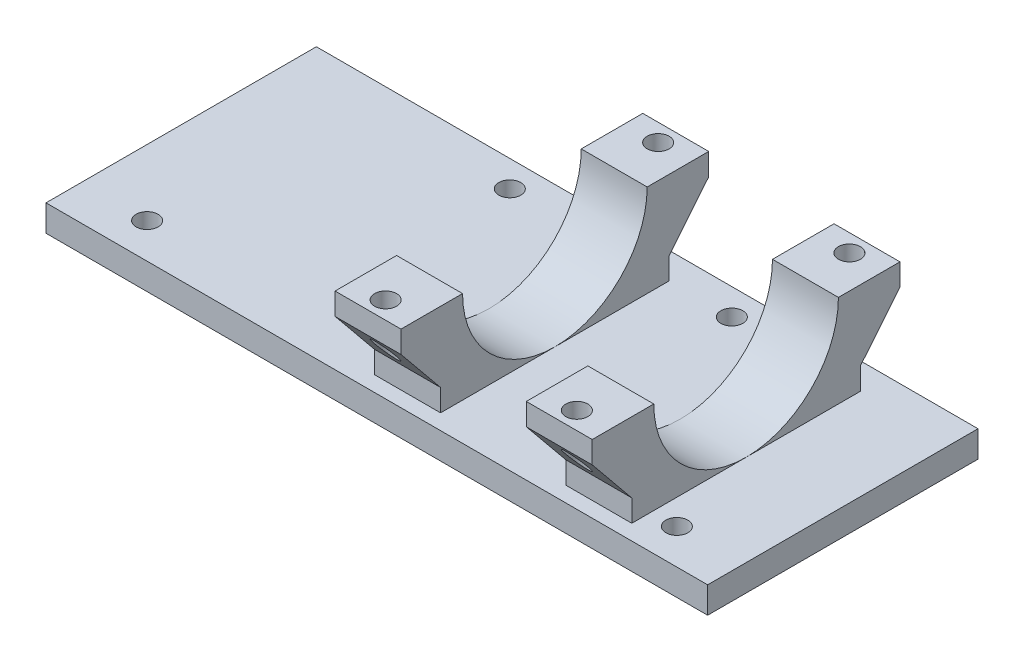
SolidWorks part; units mm, degrees
ref_plane "Alzado" through (0, 0, 0) normal (0, 0, 1) x (1, 0, 0)
ref_plane "Planta" through (0, 0, 0) normal (0, 1, 0) x (1, 0, 0)
ref_plane "Vista lateral" through (0, 0, 0) normal (1, 0, 0) x (0, 0, -1)
sketch "Croquis1" plane through (0, 0, 0) normal (0, 1, 0) x (1, 0, 0)
  line L1 (74.5, -26.5) -> (-74.5, -26.5)
  line L2 (74.5, -26.5) -> (74.5, 26.5)
  line L3 (74.5, 26.5) -> (-74.5, 26.5)
  line L4 (-74.5, -26.5) -> (-74.5, 26.5)
  line L5 (74.5, -26.5) -> (-74.5, 26.5) construction
  line L6 (74.5, 26.5) -> (-74.5, -26.5) construction
  point P0 (0, 0)
  dimension "D1" = 149
  dimension "D2" = 53
extrude "Saliente-Extruir1" add sketch "Croquis1" along normal blind 6
ref_plane "Plano1" through (51.5, 0, 0) normal (1, 0, 0) x (0, 0, -1)
sketch "Croquis2" plane through (51.5, 0, 0) normal (1, 0, 0) x (0, 0, -1)
  line L0 (-26.5, 6) -> (26.5, 6) construction
  line L1 (26, 6) -> (-26, 6)
  line L2 (26, 6) -> (26, 27)
  line L4 (-26, 6) -> (-26, 27)
  arc A0 (26, 27) -> (-26, 27) centre (0, 27) ccw
  point P6 (0, 6)
  dimension "D1" = 52
  dimension "D2" = 21
extrude "Saliente-Extruir2" add sketch "Croquis2" against normal blind 15 contours L2 A0 L4 L1
ref_plane "Plano4" through (8, 0, 0) normal (-1, 0, 0) x (0, 0, 1)
sketch "Croquis5" plane through (8, 0, 0) normal (-1, 0, 0) x (0, 0, 1)
  line L0 (-26, 6) -> (26, 6) construction
  line L1 (26, 6) -> (26, 27) construction
  line L2 (-26, 6) -> (-26, 27) construction
  line L3 (-26, 6) -> (26, 6)
  line L4 (26, 6) -> (26, 27)
  line L5 (-26, 6) -> (-26, 27)
  arc A0 (26, 27) -> (-26, 27) centre (0, 27) ccw construction
  arc A1 (26, 27) -> (-26, 27) centre (0, 27) ccw
extrude "Saliente-Extruir5" add sketch "Croquis5" along normal blind 15
sketch "Croquis3" plane through (51.5, 0, 0) normal (1, 0, 0) x (0, 0, -1)
  circle A0 centre (0, 27) radius 21
  dimension "D1" = 42
extrude "Cortar-Extruir2" cut sketch "Croquis3" against normal through all contours A0
ref_plane "Plano5" through (0, 0, 26) normal (0, 0, 1) x (1, 0, 0)
sketch "Croquis10" plane through (0, 0, 26.5) normal (0, 0, 1) x (1, 0, 0)
  line L4 (-74.5, 0) -> (74.5, 0)
  line L5 (74.5, 0) -> (74.5, 6)
  line L6 (74.5, 6) -> (-74.5, 6)
  line L7 (-74.5, 6) -> (-74.5, 0)
  line L8 (-74.5, 0) -> (74.5, 0)
  line L9 (74.5, 0) -> (74.5, 6)
  line L10 (74.5, 6) -> (-74.5, 6)
  line L11 (-74.5, 6) -> (-74.5, 0)
  dimension "D1" = 0
extrude "Saliente-Extruir23" add sketch "Croquis10" along normal blind 3
sketch "Croquis11" plane through (0, 6, 0) normal (0, 1, 0) x (1, 0, 0)
  line L0 (74.5, -29.5) -> (-74.5, -29.5) construction
  line L1 (74.5, 26.5) -> (72.25, 26.5)
  line L2 (74.5, 26.5) -> (74.5, -29.5)
  line L3 (74.5, -29.5) -> (72.25, -29.5)
  line L4 (72.25, 26.5) -> (72.25, -29.5)
  dimension "D1" = 2.25
extrude "Cortar-Extruir3" cut sketch "Croquis11" against normal through all
sketch "Croquis12" plane through (-74.5, 0, 0) normal (-1, 0, 0) x (0, 0, 1)
  line L4 (-26.5, 0) -> (29.5, 0)
  line L5 (29.5, 0) -> (29.5, 6)
  line L6 (29.5, 6) -> (-26.5, 6)
  line L7 (-26.5, 6) -> (-26.5, 0)
  line L8 (-26.5, 0) -> (29.5, 0)
  line L9 (29.5, 0) -> (29.5, 6)
  line L10 (29.5, 6) -> (-26.5, 6)
  line L11 (-26.5, 6) -> (-26.5, 0)
  dimension "D1" = 0
extrude "Saliente-Extruir24" add sketch "Croquis12" along normal blind 3.75
ref_plane "Plano6" through (-3, 0, 0) normal (1, 0, 0) x (0, 0, -1)
sketch "Croquis13" plane through (0, 6, 0) normal (0, 1, 0) x (1, 0, 0)
  line L0 (-78.25, -29.5) -> (-78.25, 26.5) construction
  line L1 (72.25, 26.5) -> (-78.25, 26.5)
  line L2 (72.25, 26.5) -> (72.25, 26)
  line L3 (72.25, 26) -> (-78.25, 26)
  line L4 (-78.25, 26.5) -> (-78.25, 26)
  line L5 (-7, 26) -> (8, 26) construction
extrude "Cortar-Extruir4" cut sketch "Croquis13" against normal through all
ref_plane "Plano7" through (0, 27, 0) normal (0, -1, 0) x (-1, 0, 0)
sketch "Croquis14" plane through (0, 27, 0) normal (0, -1, 0) x (-1, 0, 0)
  line L1 (84.7136, -38.0167) -> (-84.7136, -38.0167)
  line L2 (84.7136, -38.0167) -> (84.7136, 38.0167)
  line L3 (84.7136, 38.0167) -> (-84.7136, 38.0167)
  line L4 (-84.7136, -38.0167) -> (-84.7136, 38.0167)
  line L5 (84.7136, -38.0167) -> (-84.7136, 38.0167) construction
  line L6 (84.7136, 38.0167) -> (-84.7136, -38.0167) construction
  point P0 (0, 0)
extrude "Cortar-Extruir5" cut sketch "Croquis14" against normal through all
sketch "Croquis15" plane through (51.5, 0, 0) normal (1, 0, 0) x (0, 0, -1)
  line L0 (-26, 27) -> (-35, 27)
  line L1 (-26, 8.25) -> (-26, -8.25) construction
  line L2 (-35, 27) -> (-35, 22)
  line L3 (-35, 22) -> (-26, 11)
  line L4 (-26, 11) -> (-26, 27)
  line L5 (-26, 27) -> (-21, 27) construction
  dimension "D1" = 9
  dimension "D2" = 5
  dimension "D3" = 16
ref_plane "Plano8" through (0, 20.17, 0) normal (0, 1, 0) x (1, 0, 0)
ref_plane "Plano9" through (22.25, 0, 0) normal (-1, 0, 0) x (0, 0, 1)
extrude "Saliente-Extruir25" add sketch "Croquis15" against normal blind 15
sketch "Croquis16" plane through (0, 27, 0) normal (0, 1, 0) x (1, 0, 0)
  line L0 (36.5, -35) -> (51.5, -35) construction
  circle A0 centre (44, -31) radius 2.5
  point P4 (44, -35)
  dimension "D1" = 5
  dimension "D2" = 4
extrude "Cortar-Extruir6" cut sketch "Croquis16" against normal blind 15
mirror "Simetría1" about plane through (22.25, 0, 0) normal (-1, 0, 0) of "Cortar-Extruir6", "Saliente-Extruir25"
mirror "Simetría2" about plane through (0, 0, 0) normal (0, 0, 1) of "Simetría1", "Saliente-Extruir25", "Cortar-Extruir6"
sketch "Croquis17" plane through (0, 6, 0) normal (0, 1, 0) x (1, 0, 0)
  line L0 (-78.25, -29.5) -> (-78.25, 26) construction
  line L1 (72.25, -29.5) -> (-78.25, -29.5) construction
  circle A0 centre (-63.25, -21.5) radius 2.5
  dimension "D1" = 5
  dimension "D2" = 15
  dimension "D3" = 8
extrude "Cortar-Extruir7" cut sketch "Croquis17" against normal through all
ref_plane "Plano10" through (0, 0, 1.75) normal (0, 0, 1) x (1, 0, 0)
ref_plane "Plano11" through (-3, 0, 0) normal (1, 0, 0) x (0, 0, -1)
sketch "Croquis19" plane through (0, 0, -26) normal (0, 0, -1) x (-1, 0, 0)
  line L1 (-72.25, 6) -> (78.25, 6)
  line L2 (-72.25, 6) -> (-72.25, 0)
  line L3 (-72.25, 0) -> (78.25, 0)
  line L4 (78.25, 6) -> (78.25, 0)
extrude "Saliente-Extruir26" add sketch "Croquis19" along normal blind 6
mirror "Simetría5" about plane through (-3, 0, 0) normal (1, 0, 0) of "Cortar-Extruir7"
sketch "Croquis20" plane through (0, 6, 0) normal (0, 1, 0) x (1, 0, 0)
  line L0 (-78.25, 32) -> (72.25, 32) construction
  line L1 (36.5, 26) -> (36.5, 0) construction
  circle A0 centre (22.25, 26) radius 2.5
  point P2 (0, 0)
  dimension "D1" = 5
  dimension "D2" = 6
  dimension "D3" = 14.25
extrude "Cortar-Extruir8" cut sketch "Croquis20" against normal through all
mirror "Simetría6" about plane through (-3, 0, 0) normal (1, 0, 0) of "Cortar-Extruir8"
